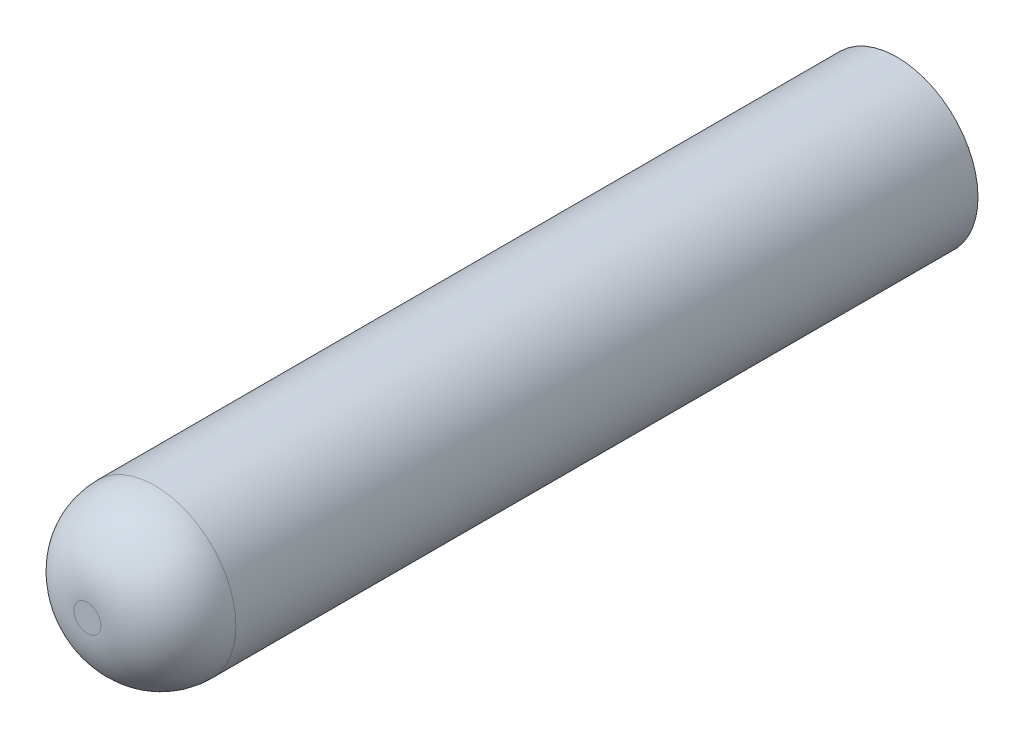
SolidWorks part; units mm, degrees
ref_plane "Front Plane" through (0, 0, 0) normal (0, 0, 1) x (1, 0, 0)
ref_plane "Top Plane" through (0, 0, 0) normal (0, 1, 0) x (1, 0, 0)
ref_plane "Right Plane" through (0, 0, 0) normal (1, 0, 0) x (0, 0, -1)
sketch "Sketch1" plane through (0, 0, 0) normal (0, 0, 1) x (1, 0, 0)
  circle A0 centre (0, 0) radius 6
  dimension "D1" = 12
extrude "Boss-Extrude1" add sketch "Sketch1" along normal blind 60
fillet "Fillet1" radius 5 1 edges at (6, 0, 60)
